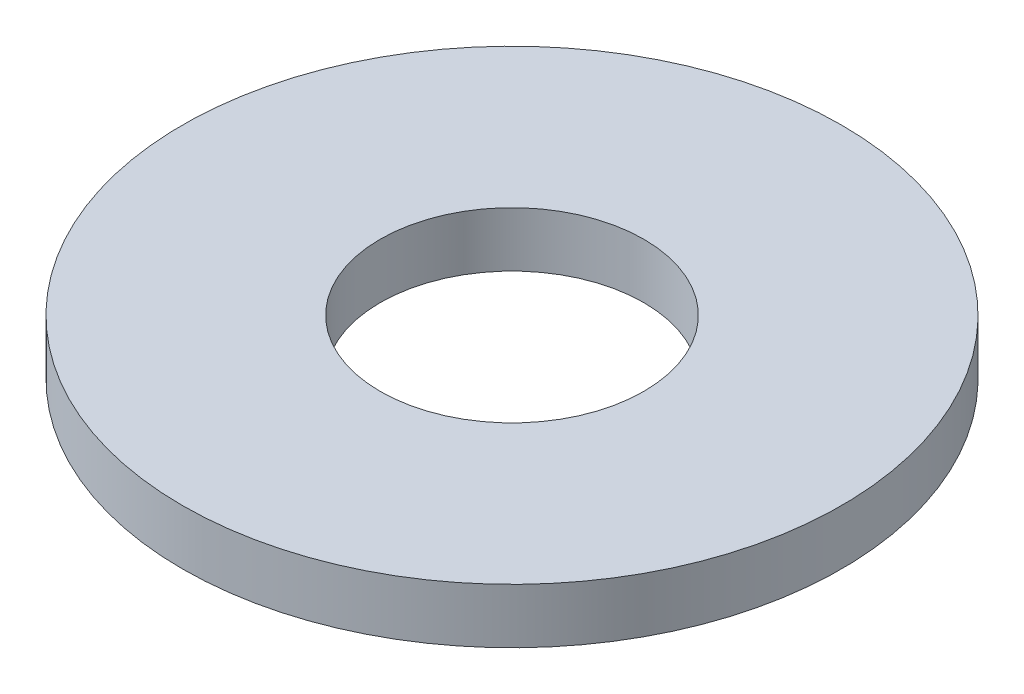
SolidWorks part; units mm, degrees
ref_plane "Front Plane" through (0, 0, 0) normal (0, 0, 1) x (1, 0, 0)
ref_plane "Top Plane" through (0, 0, 0) normal (0, 1, 0) x (1, 0, 0)
ref_plane "Right Plane" through (0, 0, 0) normal (1, 0, 0) x (0, 0, -1)
sketch "Sketch1" plane through (0, 0, 0) normal (0, 1, 0) x (1, 0, 0)
  circle A0 centre (0, 0) radius 15
  circle A1 centre (0, 0) radius 6
extrude "Boss-Extrude1" add sketch "Sketch1" along normal blind 2.5
